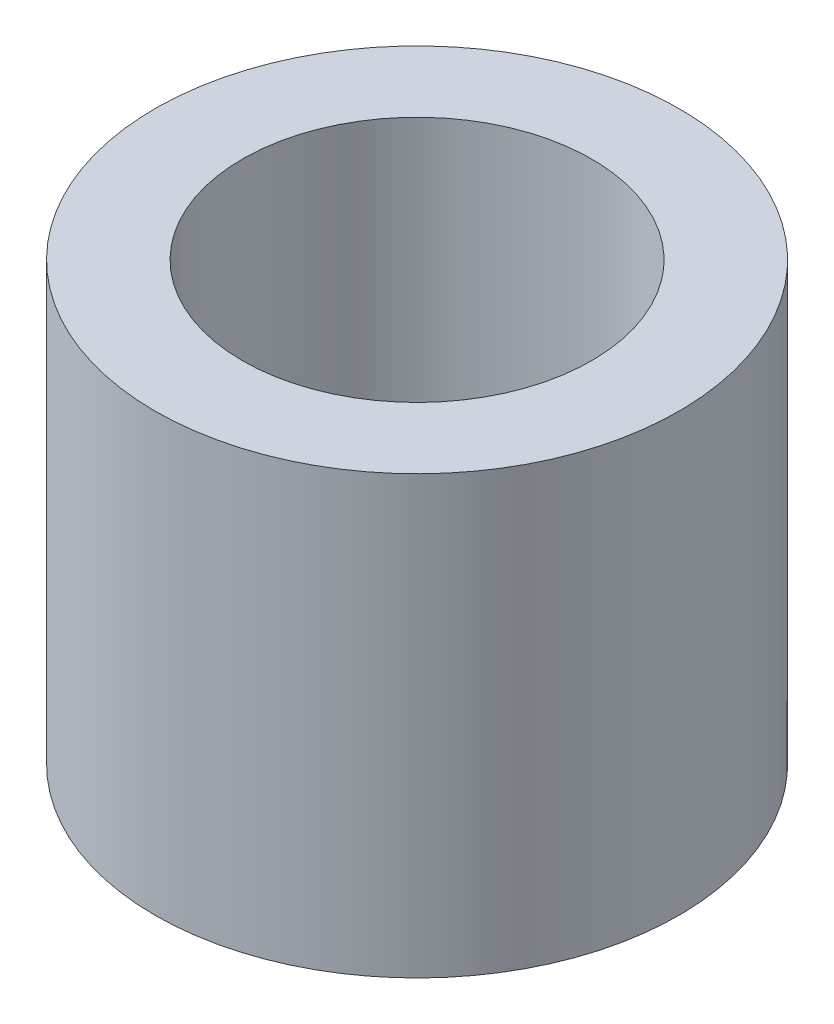
SolidWorks part; units mm, degrees
ref_plane "Front Plane" through (0, 0, 0) normal (0, 0, 1) x (1, 0, 0)
ref_plane "Top Plane" through (0, 0, 0) normal (0, 1, 0) x (1, 0, 0)
ref_plane "Right Plane" through (0, 0, 0) normal (1, 0, 0) x (0, 0, -1)
sketch "Sketch1" plane through (0, 0, 0) normal (0, 1, 0) x (1, 0, 0)
  circle A0 centre (0, 0) radius 4
  circle A1 centre (0, 0) radius 6
  dimension "D1" = 8
  dimension "D2" = 2
extrude "Boss-Extrude1" add sketch "Sketch1" along normal blind 10
